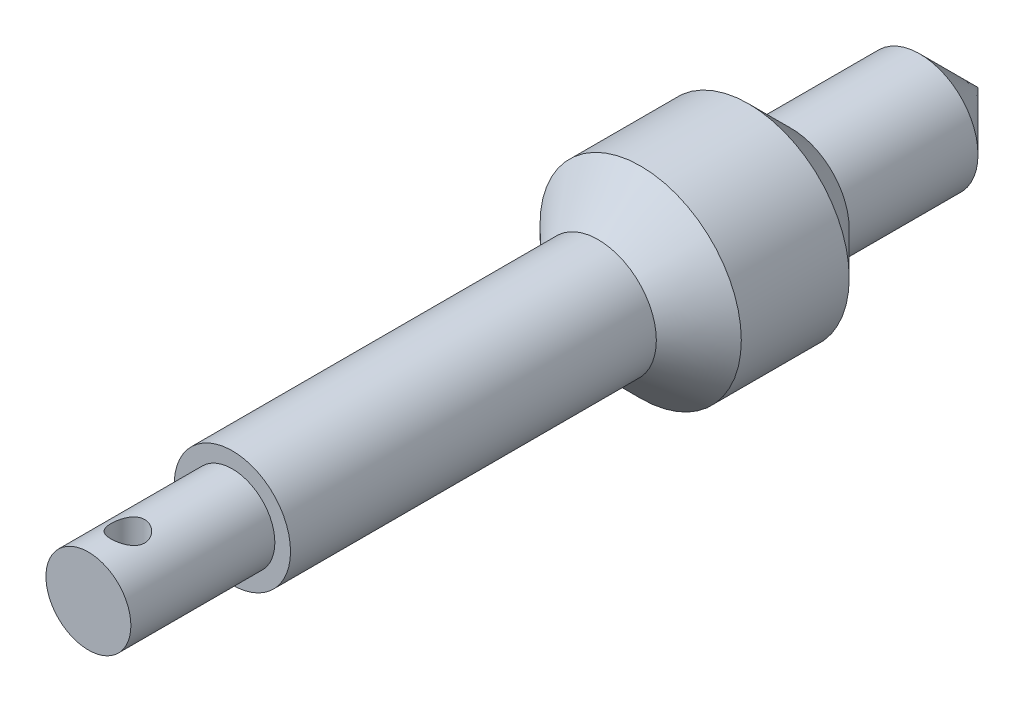
SolidWorks part; units mm, degrees
ref_plane "Front Plane" through (0, 0, 0) normal (0, 0, 1) x (1, 0, 0)
ref_plane "Top Plane" through (0, 0, 0) normal (0, 1, 0) x (1, 0, 0)
ref_plane "Right Plane" through (0, 0, 0) normal (1, 0, 0) x (0, 0, -1)
sketch "Sketch1" plane through (0, 0, 0) normal (1, 0, 0) x (0, 0, -1)
  line L0 (0, 0) -> (0, 2.7375) construction
  line L1 (0, 6.35) -> (3.175, 6.35)
  line L2 (3.175, 6.35) -> (3.175, 5.5315)
  line L3 (5.7937, 8.5) -> (5.7937, 13) construction
  line L4 (5.7937, 13) -> (0.7938, 13) construction
  line L5 (0.7938, 13) -> (0.7938, 8.5) construction
  line L6 (5.7937, 13) -> (5.7937, 14) construction
  line L7 (5.7937, 14) -> (6.7937, 14) construction
  line L8 (6.7937, 14) -> (6.7937, 7.5) construction
  line L9 (0, 8.5) -> (5.7937, 8.5)
  line L10 (0, 8.5) -> (0, 6.35) construction
  line L11 (5.7937, 8.5) -> (5.7937, 7.5)
  line L12 (5.7937, 7.5) -> (39.6687, 7.5)
  line L13 (6.7937, 14) -> (6.7937, 20.32) construction
  line L14 (6.7937, 20.32) -> (16.3187, 20.32) construction
  line L15 (16.3187, 20.32) -> (16.3187, 7.5) construction
  line L16 (11.5562, 19.5) -> (11.5562, 7.5) construction
  line L17 (11.5562, 19.5) -> (16.5562, 19.5) construction
  line L18 (16.5562, 19.5) -> (16.5562, 7.5) construction
  line L19 (9.175, 20.32) -> (9.175, 0) construction
  line L20 (16.5562, 19.5) -> (16.5562, 14) construction
  line L21 (16.5562, 14) -> (17.5562, 14) construction
  line L22 (17.5562, 14) -> (17.5562, 7.5) construction
  line L23 (0, 0) -> (31.9294, 0)
  line L24 (17.5562, 14) -> (17.5562, 26.67) construction
  line L25 (17.5562, 26.67) -> (27.0812, 26.67) construction
  line L26 (27.0812, 26.67) -> (27.0812, 7.5) construction
  line L27 (22.3187, 7.5) -> (22.3187, 19.5) construction
  line L28 (22.3187, 19.5) -> (27.3187, 19.5) construction
  line L29 (27.3187, 19.5) -> (27.3187, 7.5) construction
  line L30 (19.9375, 26.67) -> (19.9375, 0) construction
  line L31 (27.3187, 19.5) -> (27.3187, 14) construction
  line L32 (27.3187, 14) -> (28.3187, 14) construction
  line L33 (28.3187, 14) -> (28.3187, 7.5) construction
  line L34 (28.3187, 19.5) -> (33.3187, 19.5) construction
  line L35 (33.3187, 19.5) -> (33.3187, 7.5) construction
  line L36 (33.3187, 2.3813) -> (33.3187, 38.6538) construction
  line L37 (26.9687, 0) -> (26.9687, 30.1625) construction
  line L38 (28.5562, 30.1625) -> (28.5562, 0) construction
  line L39 (0, 0) -> (0, 2.7375) construction
  line L40 (6.35, 42.8625) -> (6.35, 0) construction
  line L41 (4.7625, 50.8) -> (4.7625, 0) construction
  line L42 (-17.4625, 46.0375) -> (-17.4625, 53.5375)
  line L43 (3.175, 5.5315) -> (23.1125, 5.5315)
  line L44 (0, 4.7378) -> (13.0644, 4.7378) construction
  line L45 (0, 2.7375) -> (14.0479, 2.7375)
  line L46 (11.9076, 4.7378) -> (9.9073, 2.7375) construction
  line L47 (17.2049, 4.7378) -> (19.2052, 2.7375) construction
  line L48 (21.1281, 4.7378) -> (23.1284, 2.7375)
  line L49 (16.0481, 4.7378) -> (16.0481, 0) construction
  line L50 (7.9844, 4.7378) -> (5.9841, 2.7375) construction
  line L51 (13.0644, 4.7378) -> (15.0646, 2.7375) construction
  line L52 (16.0481, 4.7378) -> (14.0479, 2.7375)
  line L53 (29.1919, 2.7375) -> (31.9294, 0)
  line L54 (16.0481, 4.7378) -> (21.1281, 4.7378)
  line L55 (39.6687, 2.3813) -> (39.6687, 7.5)
  line L56 (0, 6.35) -> (0, 44.45) construction
  line L57 (23.1284, 2.7375) -> (29.1919, 2.7375)
  line L58 (23.1125, 5.5315) -> (24.5284, 3.175)
  line L59 (24.5284, 3.175) -> (29.8649, 3.175)
  line L60 (29.8649, 3.175) -> (30.3419, 2.3813)
  line L61 (30.3419, 2.3813) -> (39.6687, 2.3813)
  line L62 (30.3419, 2.3813) -> (29.5481, 2.3813)
  line L63 (0, 2.7375) -> (-3.175, 2.7375)
  line L64 (-3.175, 2.7375) -> (-3.175, 2)
  line L65 (-3.175, 2) -> (-9.9531, 2)
  line L66 (-9.9531, 2) -> (-9.9531, 0)
  line L67 (-9.9531, 0) -> (0, 0)
  line L68 (-3.175, 2.7375) -> (-3.175, 4.5)
  line L69 (-3.175, 4.5) -> (-7.175, 4.5)
  line L70 (-7.175, 4.5) -> (-7.175, 2)
  line L71 (-3.175, 3.175) -> (-1.5875, 3.175)
  line L72 (-1.5875, 3.175) -> (-1.5875, 8.5)
  line L73 (-1.5875, 8.5) -> (-13.9219, 8.5)
  line L74 (-12.3344, 3.429) -> (-12.3344, 3.81)
  line L75 (-12.3344, 3.81) -> (-7.175, 3.81)
  line L76 (-7.302, 0) -> (-7.302, 3.175)
  line L77 (-7.302, 3.175) -> (-8.8895, 3.175)
  line L78 (-8.8895, 3.175) -> (-8.8895, 0)
  line L79 (-10.35, 0) -> (-10.35, 3.429)
  line L80 (-10.35, 3.429) -> (-12.3344, 3.429)
  line L81 (-12.3344, 3.429) -> (-12.3344, 0)
  line L82 (-12.3344, 0) -> (-10.35, 0)
  line L83 (-7.175, 4.5) -> (-7.175, 6.985)
  line L84 (-7.175, 6.985) -> (-13.9219, 6.985)
  line L85 (-13.9219, 6.985) -> (-13.9219, 8.5)
  line L86 (-13.9219, 2.0828) -> (-13.9219, 6.985)
  line L87 (-12.3344, 2.0828) -> (-13.9219, 2.0828)
  circle A0 centre (-17.4625, 46.0375) radius 7.5
  circle A1 centre (-17.4625, 46.0375) radius 5.5315
  circle A2 centre (-17.4625, 53.1565) radius 2.3812
  circle A3 centre (-17.4625, 51.1562) radius 2.3812
  circle A4 centre (-17.4625, 46.0375) radius 12.7
  arc A5 (-14.9548, 53.1058) -> (-19.9702, 53.1058) centre (-17.4625, 53.1565) ccw
  circle A6 centre (-17.4625, 46.0375) radius 2.7375
  circle A7 centre (-17.4625, 46.0375) radius 4.7378
  circle A8 centre (-17.4625, 46.0375) radius 7.754
  circle A9 centre (9.175, 7.119) radius 2.3813 construction
  circle A10 centre (9.175, 5.3727) radius 2.3813 construction
  circle A11 centre (9.175, 5.1187) radius 2.3813 construction
  circle A12 centre (19.9375, 7.119) radius 2.3813 construction
  circle A13 centre (19.9375, 5.3727) radius 2.3813 construction
  circle A14 centre (19.9375, 5.1187) radius 2.3813 construction
  dimension "D24" = 15
  dimension "D25" = 4.7625
  dimension "D27" = 25.4
  dimension "D28" = 5.0165
  dimension "D29" = 0.7937
  dimension "D30" = 0.254
  dimension "D31" = 11.063
  dimension "D32" = 5.475
  dimension "D34" = 9.4755
  dimension "D37" = 4.7625
  dimension "D39" = 2.1273
  dimension "D1" = 8.5
  dimension "D2" = 3.175
  dimension "D3" = 6.35
  dimension "D4" = 5.7937
  dimension "D5" = 7.5
  dimension "D6" = 5
  dimension "D7" = 13
  dimension "D8" = 1
  dimension "D9" = 14
  dimension "D10" = 9.525
  dimension "D11" = 20.32
  dimension "D12" = 4.7625
  dimension "D13" = 5
  dimension "D14" = 2.3813
  dimension "D15" = 12
  dimension "D16" = 26.67
  dimension "D17" = 4.7625
  dimension "D18" = 2.3813
  dimension "D19" = 6.35
  dimension "D20" = 1.5875
  dimension "D21" = 6.35
  dimension "D22" = 1.5875
  dimension "D23" = 6.35
  dimension "D26" = 0.381
  dimension "D33" = 5.5315
  dimension "D35" = 4.7378
  dimension "D36" = 2.7375
  dimension "D38" = 0.381
  dimension "D40" = 45
  dimension "D41" = 5.2973
  dimension "D42" = 10.7625
  dimension "D43" = 1.1906
  dimension "D44" = 5.08
  dimension "D45" = 1.1906
  dimension "D46" = 8.0637
  dimension "D47" = 5.08
  dimension "D48" = 6.0635
  dimension "D49" = 45
  dimension "D50" = 6.0635
  dimension "D51" = 0.7937
  dimension "D52" = 59
  dimension "D53" = 3.175
  dimension "D54" = 0.7937
  dimension "D55" = 2.3813
  dimension "D56" = 2
  dimension "D57" = 4.5
  dimension "D58" = 4
  dimension "D59" = 1.5875
  dimension "D60" = 4.69
  dimension "D61" = 1.5875
  dimension "D62" = 1.9844
  dimension "D63" = 3.429
  dimension "D64" = 2.7781
  dimension "D65" = 1.5875
  dimension "D66" = 3.175
  dimension "D67" = 0.127
  dimension "D68" = 0.3969
  dimension "D69" = 1.5875
  dimension "D70" = 3.81
  dimension "D71" = 3.175
  dimension "D72" = 2.0828
  dimension "D73" = 12.3344
revolve "Revolve2" add sketch "Sketch1" angle 360 about L23
sketch "Sketch2" plane through (0, 0, 0) normal (0, 1, 0) x (1, 0, 0)
  line L0 (-2.7375, -3.175) -> (2.7375, -3.175) construction
  line L1 (-2, -9.9531) -> (2, -9.9531) construction
  line L2 (-2.7375, -3.175) -> (2.7375, -3.175)
  line L3 (-2, -9.9531) -> (2, -9.9531)
  line L4 (0, -3.175) -> (0, -9.9531)
  circle A0 centre (0, -8.0958) radius 0.7937
  dimension "D1" = 1.5875
  dimension "D2" = 4.9208
extrude "Cut-Extrude1" cut sketch "Sketch2" against normal through all both and the other way through all contours L4 A0 | L4 A0
ref_plane "Plane1" through (0, 0, -21.1281) normal (0, 0, 1) x (1, 0, 0)
equation "\"D1@Sketch1\"=(17mm/2)"
equation "\"D5@Sketch1\"=15mm/2"
equation "\"D4@Sketch1\"=5mm+1/32"
equation "\"D6@Sketch1\"=5mm"
equation "\"D7@Sketch1\"=26mm/2"
equation "\"D8@Sketch1\"=1mm"
equation "\"D9@Sketch1\"=28mm/2"
equation "\"D11@Sketch1\"=(34-2)/20/2"
equation "\"D13@Sketch1\"=5mm"
equation "\"D15@Sketch1\"=24mm/2"
equation "\"D16@Sketch1\"=(44-2)/20/2"
equation "\"D33@Sketch1\"=\"D31@Sketch1\"/2"
equation "\"D35@Sketch1\"= \"D34@Sketch1\" / 2"
equation "\"D36@Sketch1\"= \"D32@Sketch1\" / 2"
equation "\"D39@Sketch1\" = \"D37@Sketch1\"/2-.01"
equation "\"D45@Sketch1\" = 3 / 64"
equation "\"D43@Sketch1\" = \"D45@Sketch1\""
equation "\"D47@Sketch1\"=\"D44@Sketch1\""
equation "\"D56@Sketch1\"=2mm"
equation "\"D57@Sketch1\"=9mm/2"
equation "\"D58@Sketch1\"=4mm"
equation "\"D63@Sketch1\"=.27/2"
equation "\"D64@Sketch1\"=1/16+3/64"
equation "\"D2@Sketch2\"=4mm+\"D1@Sketch2\"/2+.005"
